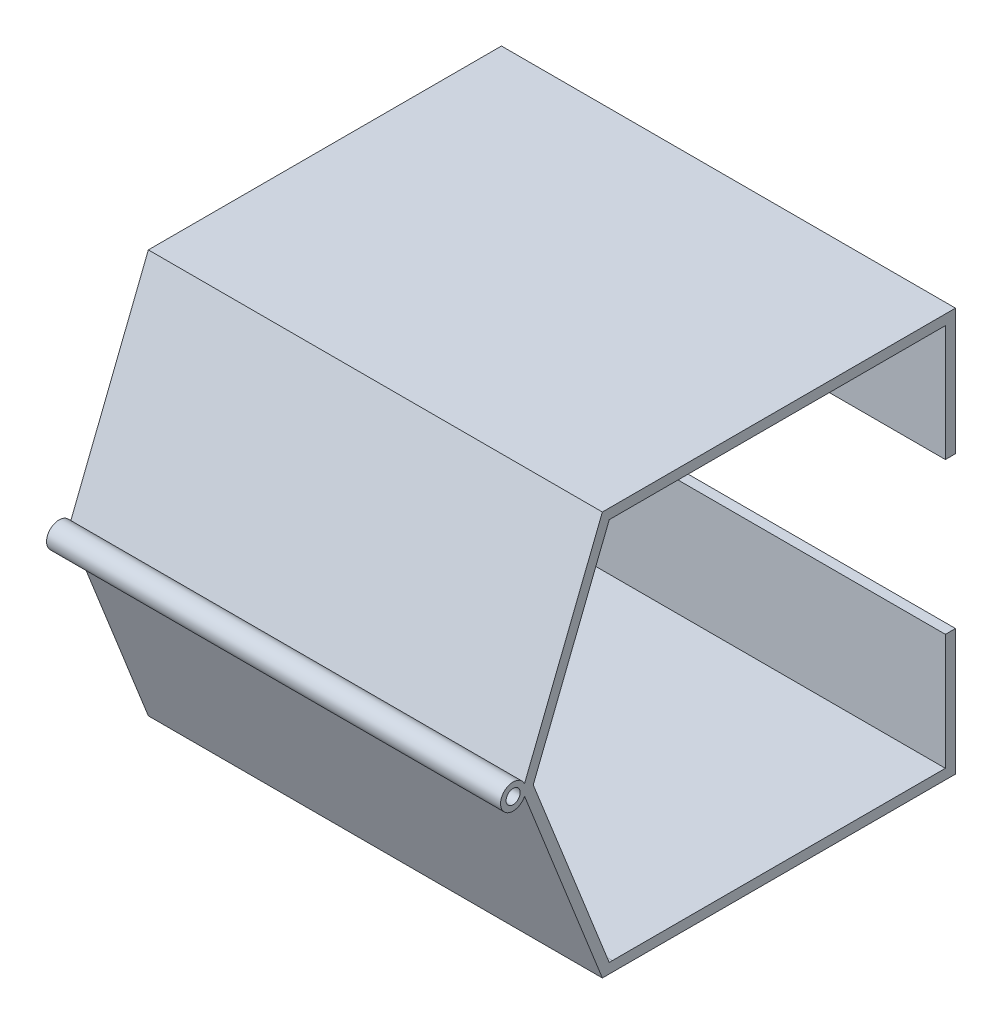
SolidWorks part; units mm, degrees
ref_plane "Front Plane" through (0, 0, 0) normal (0, 0, 1) x (1, 0, 0)
ref_plane "Top Plane" through (0, 0, 0) normal (0, 1, 0) x (1, 0, 0)
ref_plane "Right Plane" through (0, 0, 0) normal (1, 0, 0) x (0, 0, -1)
sketch "Sketch1" plane through (0, 0, 0) normal (0, 0, 1) x (1, 0, 0)
  line L1 (-45, 40) -> (45, 40)
  line L2 (-45, 40) -> (-45, -40)
  line L3 (-45, -40) -> (45, -40)
  line L4 (45, 40) -> (45, -40)
  line L5 (-45, 40) -> (45, -40) construction
  line L6 (-45, -40) -> (45, 40) construction
  point P0 (0, 0)
  dimension "D1" = 90
  dimension "D2" = 80
extrude "Boss-Extrude4" add sketch "Sketch1" along normal blind 70 contours L1 L4 L3 L2
sketch "Sketch8" plane through (-45, 0, 0) normal (-1, 0, 0) x (0, 0, 1)
  line L5 (70, 40) -> (85.8525, 0)
  line L6 (85.8525, 0) -> (70, -40)
  line L7 (70, -40) -> (70, 40)
  point P2 (70, 0)
  dimension "D2" = 40
extrude "Boss-Extrude5" add sketch "Sketch8" against normal through all contours L6 L7 L5
sketch "Sketch9" plane through (-45, 0, 0) normal (-1, 0, 0) x (0, 0, 1)
  circle A0 centre (87.6854, 0) radius 2.5
  circle A1 centre (87.6854, 0) radius 1.4
  dimension "D1" = 5
  dimension "D2" = 2.8
extrude "Boss-Extrude6" add sketch "Sketch9" against normal through all
sketch "Sketch10" plane through (-45, 0, 0) normal (-1, 0, 0) x (0, 0, 1)
  line L0 (0, 40) -> (0, -40) construction
  line L1 (2, 38) -> (68, 38)
  line L2 (2, 38) -> (2, -38)
  line L3 (2, -38) -> (68, -38)
  line L4 (68, 38) -> (68, -38)
  line L5 (2, 38) -> (68, -38) construction
  line L6 (2, -38) -> (68, 38) construction
  line L7 (70, 40) -> (0, 40) construction
  point P0 (35, 0)
  dimension "D1" = 66
  dimension "D2" = 76
  dimension "D3" = 35
  dimension "D4" = 2
extrude "Cut-Extrude1" cut sketch "Sketch10" against normal through all
sketch "Sketch11" plane through (45, 0, 0) normal (1, 0, 0) x (0, 0, -1)
  line L2 (-68.1407, 39.2631) -> (-83.568, 0.336)
  line L3 (-68.6412, 38.0003) -> (-83.7012, 0)
  line L4 (-68.6404, -38.0022) -> (-68, -38)
  line L5 (-83.568, -0.336) -> (-68.1407, -39.2631)
  line L6 (-83.7012, 0) -> (-68.6404, -38.0022)
  line L7 (-68.6412, 38.0003) -> (-68, 38)
  line L8 (-68, 38) -> (-68, -38)
  dimension "D1" = 2
  dimension "D2" = 2
extrude "Cut-Extrude2" cut sketch "Sketch11" against normal through all
sketch "Sketch16" plane through (0, 0, 0) normal (0, 0, -1) x (-1, 0, 0)
  line L0 (-45, -15) -> (-45, 15)
  line L1 (-45, 15) -> (45, 15)
  line L2 (45, 15) -> (45, -15)
  line L3 (45, -15) -> (-45, -15)
extrude "Cut-Extrude3" cut sketch "Sketch16" against normal blind 10
